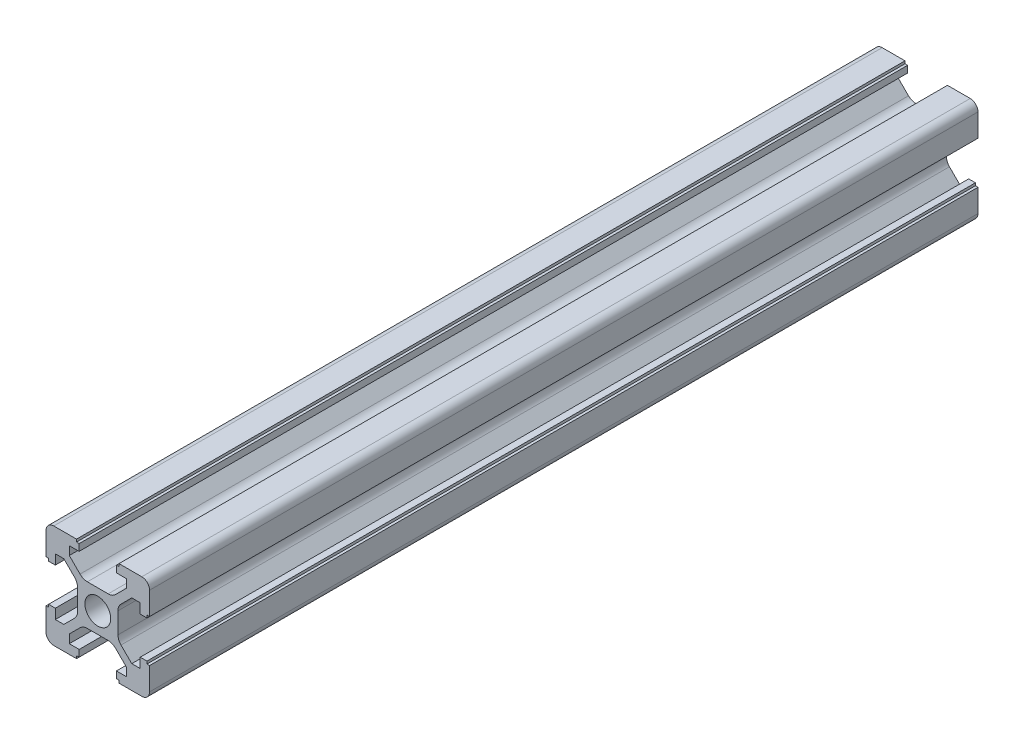
SolidWorks part; units mm, degrees
material "6063-O"
ref_plane "Front Plane" through (0, 0, 0) normal (0, 0, 1) x (1, 0, 0)
ref_plane "Top Plane" through (0, 0, 0) normal (0, 1, 0) x (1, 0, 0)
ref_plane "Right Plane" through (0, 0, 0) normal (1, 0, 0) x (0, 0, -1)
sketch "Sketch1" plane through (0, 0, 0) normal (0, 0, 1) x (1, 0, 0)
  line L0 (10, -4.1) -> (10, -8.5)
  line L1 (4.1, 10) -> (8.5, 10)
  line L2 (8.5, -10) -> (4.1, -10)
  line L3 (-8.5, -10) -> (-4.1, -10)
  line L4 (10, 8.5) -> (10, 4.1)
  line L7 (8.5, 10) -> (4.1, 10)
  line L8 (5.5, 6.5607) -> (3.4251, 4.4858)
  line L9 (8.5, 10) -> (4.1, 10)
  line L10 (3.9, 2.0109) -> (3.9, -2.0109)
  line L11 (2.0109, -3.9) -> (-2.0109, -3.9)
  line L12 (-3.9, -2.0109) -> (-3.9, 2.0109)
  line L13 (-2.0109, 3.9) -> (2.8393, 3.9)
  line L14 (2.5, 0) -> (22.2403, 0) construction
  line L15 (3.6, 9.5) -> (3.6, 8.2)
  line L16 (9.5, 3.6) -> (8.2, 3.6)
  line L17 (8.2, 3.6) -> (8.2, 5.5)
  line L18 (8.2, 5.5) -> (6.5607, 5.5)
  line L19 (10, -4.1) -> (10, -8.5)
  line L20 (4.1, 9.5) -> (3.6, 9.5)
  line L21 (4.1, 10) -> (4.1, 9.5)
  line L22 (8.5, 10) -> (4.1, 10)
  line L23 (10, 4.1) -> (9.5, 4.1)
  line L24 (9.5, 4.1) -> (9.5, 3.6)
  line L25 (5.5, 8.2) -> (5.5, 6.5607)
  line L26 (3.6, 8.2) -> (5.5, 8.2)
  line L27 (4.4858, 3.4251) -> (6.5607, 5.5)
  line L28 (10, -8.5) -> (10, -4.1)
  line L29 (6.5607, -5.5) -> (4.4858, -3.4251)
  line L30 (10, -8.5) -> (10, -4.1)
  line L31 (2.0109, -3.9) -> (-2.0109, -3.9)
  line L32 (3.9, 2.8393) -> (3.9, -2.0109)
  line L33 (9.5, -3.6) -> (8.2, -3.6)
  line L34 (3.6, -9.5) -> (3.6, -8.2)
  line L35 (3.6, -8.2) -> (5.5, -8.2)
  line L36 (5.5, -8.2) -> (5.5, -6.5607)
  line L37 (9.5, -4.1) -> (9.5, -3.6)
  line L38 (10, -4.1) -> (9.5, -4.1)
  line L39 (10, -8.5) -> (10, -4.1)
  line L40 (4.1, -10) -> (4.1, -9.5)
  line L41 (4.1, -9.5) -> (3.6, -9.5)
  line L42 (8.2, -5.5) -> (6.5607, -5.5)
  line L43 (8.2, -3.6) -> (8.2, -5.5)
  line L44 (3.4251, -4.4858) -> (5.5, -6.5607)
  line L45 (-4.1, -10) -> (-8.5, -10)
  line L46 (-10, -8.5) -> (-10, -4.1)
  line L47 (-8.5, -10) -> (-4.1, -10)
  line L48 (-5.5, -6.5607) -> (-3.4251, -4.4858)
  line L49 (-8.5, -10) -> (-4.1, -10)
  line L50 (-3.9, -2.0109) -> (-3.9, 2.0109)
  line L51 (2.0109, -3.9) -> (-2.0109, -3.9)
  line L52 (-3.6, -9.5) -> (-3.6, -8.2)
  line L53 (-9.5, -3.6) -> (-8.2, -3.6)
  line L54 (-8.2, -3.6) -> (-8.2, -5.5)
  line L55 (-8.2, -5.5) -> (-6.5607, -5.5)
  line L56 (-4.1, -9.5) -> (-3.6, -9.5)
  line L57 (-4.1, -10) -> (-4.1, -9.5)
  line L58 (-8.5, -10) -> (-4.1, -10)
  line L59 (-10, -4.1) -> (-9.5, -4.1)
  line L60 (-9.5, -4.1) -> (-9.5, -3.6)
  line L61 (-5.5, -8.2) -> (-5.5, -6.5607)
  line L62 (-3.6, -8.2) -> (-5.5, -8.2)
  line L63 (-4.4858, -3.4251) -> (-6.5607, -5.5)
  line L64 (-10, 4.1) -> (-10, 8.5)
  line L65 (-8.5, 10) -> (-4.1, 10)
  line L66 (-10, 8.5) -> (-10, 4.1)
  line L67 (-6.5607, 5.5) -> (-4.4858, 3.4251)
  line L68 (-10, 8.5) -> (-10, 4.1)
  line L69 (-2.0109, 3.9) -> (2.0109, 3.9)
  line L70 (-3.9, -2.0109) -> (-3.9, 2.0109)
  line L71 (-9.5, 3.6) -> (-8.2, 3.6)
  line L72 (-3.6, 9.5) -> (-3.6, 8.2)
  line L73 (-3.6, 8.2) -> (-5.5, 8.2)
  line L74 (-5.5, 8.2) -> (-5.5, 6.5607)
  line L75 (-9.5, 4.1) -> (-9.5, 3.6)
  line L76 (-10, 4.1) -> (-9.5, 4.1)
  line L77 (-10, 8.5) -> (-10, 4.1)
  line L78 (-4.1, 10) -> (-4.1, 9.5)
  line L79 (-4.1, 9.5) -> (-3.6, 9.5)
  line L80 (-8.2, 5.5) -> (-6.5607, 5.5)
  line L81 (-8.2, 3.6) -> (-8.2, 5.5)
  line L82 (-3.4251, 4.4858) -> (-5.5, 6.5607)
  line L83 (4.1, -10) -> (8.5, -10)
  arc A0 (2.0109, -3.9) -> (3.4251, -4.4858) centre (2.0109, -5.9) cw
  arc A1 (4.4858, -3.4251) -> (3.9, -2.0109) centre (5.9, -2.0109) cw
  arc A2 (3.9, 2.0109) -> (4.4858, 3.4251) centre (5.9, 2.0109) cw
  arc A3 (2.0109, 3.9) -> (3.4251, 4.4858) centre (2.0109, 5.9) ccw
  arc A4 (-2.0109, 3.9) -> (-3.4251, 4.4858) centre (-2.0109, 5.9) cw
  arc A5 (-4.4858, 3.4251) -> (-3.9, 2.0109) centre (-5.9, 2.0109) cw
  arc A6 (-3.4251, -4.4858) -> (-2.0109, -3.9) centre (-2.0109, -5.9) cw
  arc A7 (-3.9, -2.0109) -> (-4.4858, -3.4251) centre (-5.9, -2.0109) cw
  circle A8 centre (0, 0) radius 2.5
  arc A9 (-8.5, -10) -> (-10, -8.5) centre (-8.5, -8.5) cw
  arc A10 (-10, 8.5) -> (-8.5, 10) centre (-8.5, 8.5) cw
  arc A11 (8.5, 10) -> (10, 8.5) centre (8.5, 8.5) cw
  arc A12 (8.5, -10) -> (10, -8.5) centre (8.5, -8.5) ccw
  point P0 (0, 0)
  point P86 (0, 0)
  point P107 (10, -10)
  dimension "D3" = 2
  dimension "D5" = 5
  dimension "D2" = 1.5
  dimension "D8" = 1.5
  dimension "D6" = 4
  dimension "D7" = 6.1
  dimension "D11" = 0.5
  dimension "D12" = 0.5
extrude "Boss-Extrude2" add sketch "Sketch1" along normal blind 160
